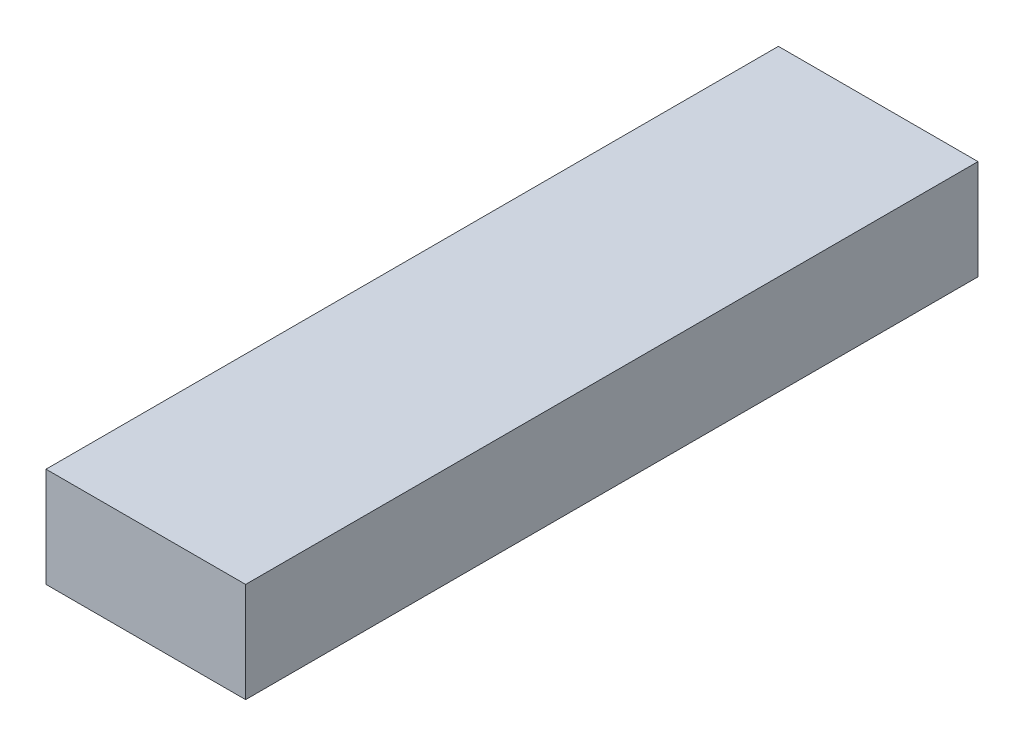
SolidWorks part; units mm, degrees
ref_plane "Front Plane" through (0, 0, 0) normal (0, 0, 1) x (1, 0, 0)
ref_plane "Top Plane" through (0, 0, 0) normal (0, 1, 0) x (1, 0, 0)
ref_plane "Right Plane" through (0, 0, 0) normal (1, 0, 0) x (0, 0, -1)
sketch "Sketch1" plane through (0, 0, 0) normal (0, 1, 0) x (1, 0, 0)
  line L1 (-4, 14.676) -> (4, 14.676)
  line L2 (-4, 14.676) -> (-4, -14.676)
  line L3 (-4, -14.676) -> (4, -14.676)
  line L4 (4, 14.676) -> (4, -14.676)
  line L5 (-4, 14.676) -> (4, -14.676) construction
  line L6 (-4, -14.676) -> (4, 14.676) construction
  point P0 (0, 0)
  dimension "D1" = 8
extrude "Boss-Extrude1" add sketch "Sketch1" along normal blind 4
sketch "Sketch3" plane through (0, 0, 0) normal (0, -1, 0) x (-1, 0, 0)
  line L0 (4, -14.676) -> (-4, -14.676) construction
  point P0 (0, -14.676)
  point P1 (0, 0)
  dimension "D1" = 4
